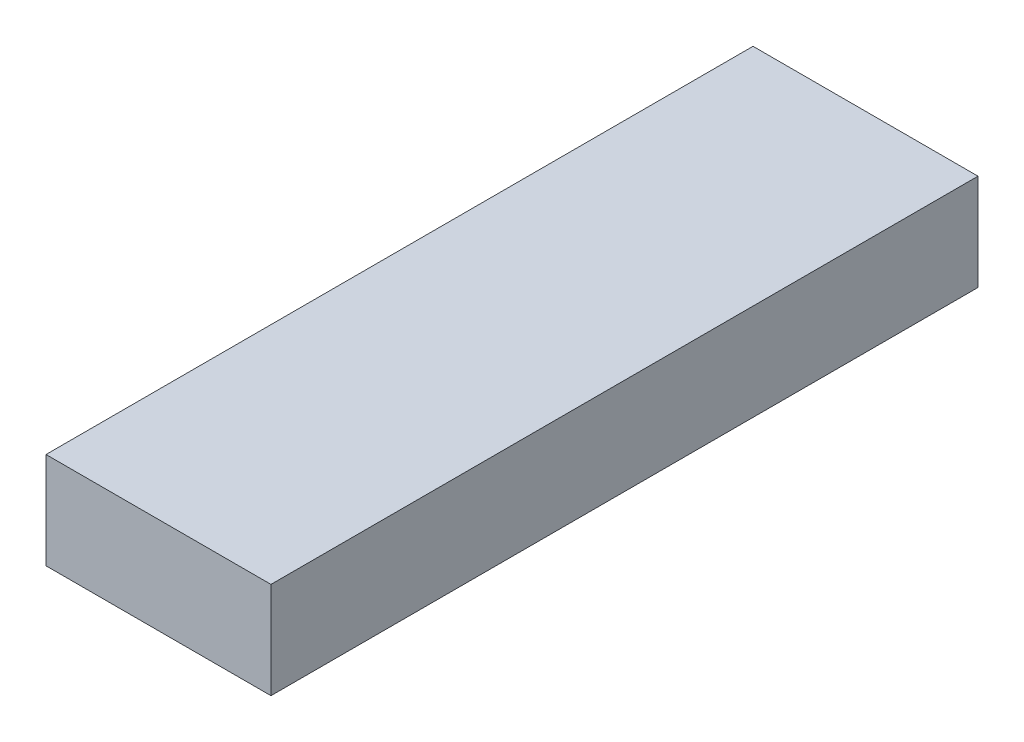
SolidWorks part; units mm, degrees
ref_plane "Front Plane" through (0, 0, 0) normal (0, 0, 1) x (1, 0, 0)
ref_plane "Top Plane" through (0, 0, 0) normal (0, 1, 0) x (1, 0, 0)
ref_plane "Right Plane" through (0, 0, 0) normal (1, 0, 0) x (0, 0, -1)
sketch "Sketch1" plane through (0, 0, 0) normal (0, 0, 1) x (1, 0, 0)
  line L1 (0, 0) -> (88.9, 0)
  line L2 (0, 0) -> (0, 38.1)
  line L3 (0, 38.1) -> (88.9, 38.1)
  line L4 (88.9, 0) -> (88.9, 38.1)
  dimension "D1" = 88.9
  dimension "D2" = 38.1
extrude "Boss-Extrude1" add sketch "Sketch1" along normal blind 279.4
